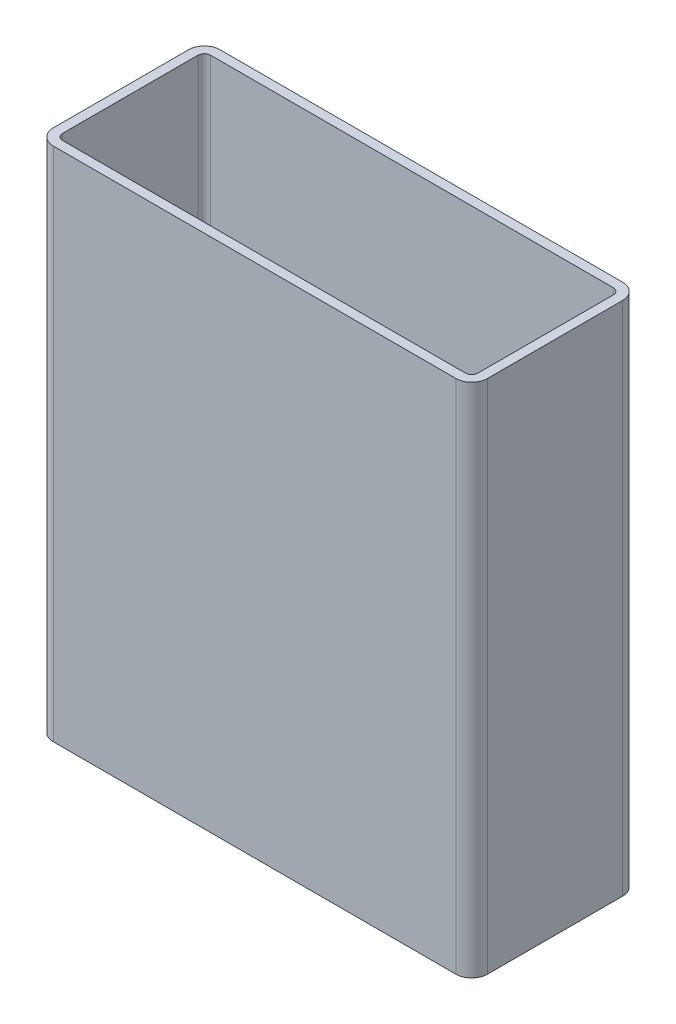
SolidWorks part; units mm, degrees
ref_plane "Спереди" through (0, 0, 0) normal (0, 0, 1) x (1, 0, 0)
ref_plane "Сверху" through (0, 0, 0) normal (0, 1, 0) x (1, 0, 0)
ref_plane "Справа" through (0, 0, 0) normal (1, 0, 0) x (0, 0, -1)
sketch "Sketch1" plane through (0, 0, 0) normal (0, 1, 0) x (1, 0, 0)
  line L1 (-6.4, -2.65) -> (6.4, -2.65)
  line L2 (-6.9, -2.15) -> (-6.9, 2.15)
  line L3 (-6.4, 2.65) -> (6.4, 2.65)
  line L4 (6.9, -2.15) -> (6.9, 2.15)
  line L5 (-6.9, -2.65) -> (6.9, 2.65) construction
  line L6 (-6.9, 2.65) -> (6.9, -2.65) construction
  arc A0 (6.4, -2.65) -> (6.9, -2.15) centre (6.4, -2.15) ccw
  arc A1 (6.4, 2.65) -> (6.9, 2.15) centre (6.4, 2.15) cw
  arc A2 (-6.4, -2.65) -> (-6.9, -2.15) centre (-6.4, -2.15) cw
  arc A3 (-6.9, 2.15) -> (-6.4, 2.65) centre (-6.4, 2.15) cw
  point P0 (0, 0)
  dimension "D3" = 0.5
  dimension "D1" = 13.8
  dimension "D2" = 5.3
extrude "Boss-Extrude1" add sketch "Sketch1" along normal blind 16.4
sketch "Sketch2" plane through (0, 16.4, 0) normal (0, 1, 0) x (1, 0, 0)
  line L0 (6.4, 2.35) -> (-6.4, 2.35)
  line L1 (-6.6, 2.15) -> (-6.6, -2.15)
  line L2 (-6.4, -2.35) -> (6.4, -2.35)
  line L3 (6.6, -2.15) -> (6.6, 2.15)
  arc A0 (-6.4, 2.35) -> (-6.6, 2.15) centre (-6.4, 2.15) ccw
  arc A1 (-6.6, -2.15) -> (-6.4, -2.35) centre (-6.4, -2.15) ccw
  arc A2 (6.4, -2.35) -> (6.6, -2.15) centre (6.4, -2.15) ccw
  arc A3 (6.6, 2.15) -> (6.4, 2.35) centre (6.4, 2.15) ccw
extrude "Cut-Extrude1" cut sketch "Sketch2" against normal blind 14.5
